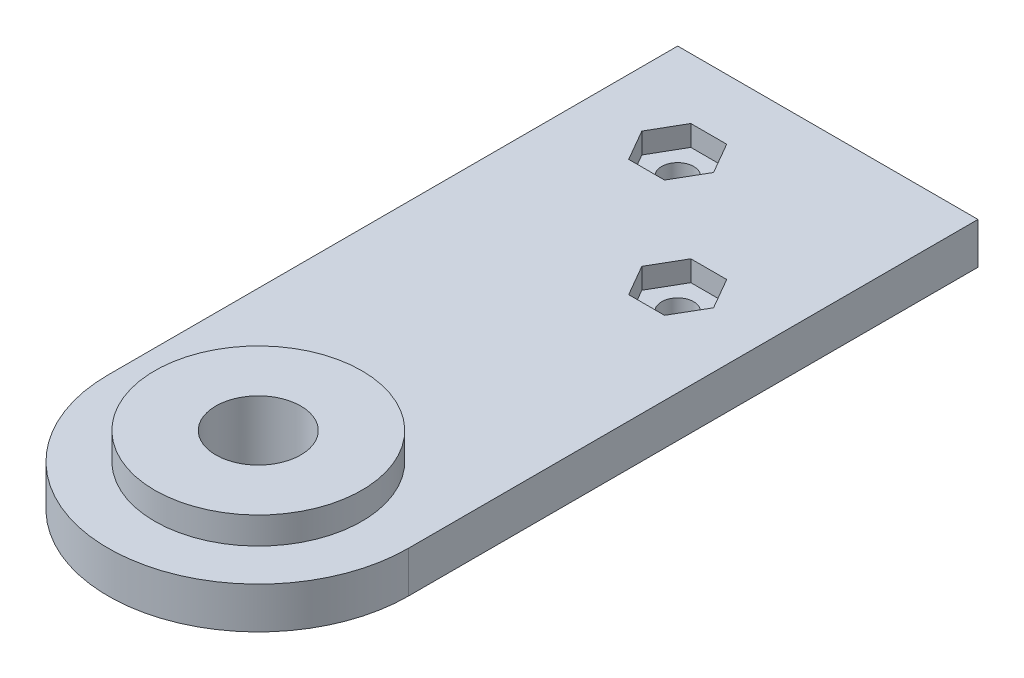
SolidWorks part; units mm, degrees
ref_plane "Front Plane" through (0, 0, 0) normal (0, 0, 1) x (1, 0, 0)
ref_plane "Top Plane" through (0, 0, 0) normal (0, 1, 0) x (1, 0, 0)
ref_plane "Right Plane" through (0, 0, 0) normal (1, 0, 0) x (0, 0, -1)
sketch "Sketch1" plane through (0, 0, 0) normal (0, 1, 0) x (1, 0, 0)
  line L1 (-46.1225, -21.4958) -> (3.8775, -21.4958)
  line L2 (-46.1225, -21.4958) -> (-46.1225, -71.4958)
  line L3 (-46.1225, -71.4958) -> (3.8775, -71.4958)
  line L4 (3.8775, -21.4958) -> (3.8775, -71.4958)
  dimension "D1" = 50
  dimension "D2" = 50
extrude "Boss-Extrude1" add sketch "Sketch1" along normal blind 4
sketch "Sketch2" plane through (0, 0, 0) normal (0, -1, 0) x (1, 0, 0)
  line L0 (3.8775, 71.4958) -> (3.8775, 21.4958) construction
  line L1 (-46.1225, 71.4958) -> (3.8775, 71.4958) construction
  circle A0 centre (-21.1225, 46.4958) radius 4.1
  point P5 (3.8775, 46.4958)
  point P9 (-21.1225, 71.4958)
  dimension "D1" = 8.2
extrude "Cut-Extrude1" cut sketch "Sketch2" against normal up to surface (4 mm away) up to face at (-21.1225, 4, 46.4958)
sketch "Sketch5" plane through (0, 4, 0) normal (0, 1, 0) x (1, 0, 0)
  circle A0 centre (-21.1225, -46.4958) radius 10
  circle A1 centre (-21.1225, -46.4958) radius 4.1
  dimension "D1" = 20
  dimension "D2" = 8.2
extrude "Boss-Extrude4" add sketch "Sketch5" along normal blind 2.6
sketch "Sketch6" plane through (0, 0, 0) normal (0, -1, 0) x (1, 0, 0)
  line L0 (-35.6225, 46.4958) -> (-35.6225, 21.4958)
  line L1 (3.8775, 21.4958) -> (-46.1225, 21.4958) construction
  line L2 (-35.6225, 21.4958) -> (-6.6225, 21.4958)
  line L3 (-6.6225, 21.4958) -> (-6.6225, 46.4958)
  arc A0 (-6.6225, 46.4958) -> (-35.6225, 46.4958) centre (-21.1225, 46.4958) ccw
extrude "Cut-Extrude3" cut sketch "Sketch6" against normal up to surface (4 mm away) flip side to cut up to face at (-21.1225, 4, 46.4958)
sketch "Sketch7" plane through (0, 0, 21.4958) normal (0, 0, -1) x (-1, 0, 0)
  line L4 (6.6225, 4) -> (6.6225, 0)
  line L5 (6.6225, 0) -> (35.6225, 0)
  line L6 (35.6225, 0) -> (35.6225, 4)
  line L7 (35.6225, 4) -> (6.6225, 4)
  line L8 (6.6225, 4) -> (6.6225, 0)
  line L9 (6.6225, 0) -> (35.6225, 0)
  line L10 (35.6225, 0) -> (35.6225, 4)
  line L11 (35.6225, 4) -> (6.6225, 4)
  dimension "D1" = 0
extrude "Boss-Extrude5" add sketch "Sketch7" along normal blind 30
sketch "Sketch8" plane through (0, 4, 0) normal (0, 1, 0) x (1, 0, 0)
  line L0 (-35.6225, 8.5042) -> (-6.6225, -20.4958) construction
  line L1 (-6.6225, 8.5042) -> (-6.6225, -46.4958) construction
  line L2 (-15.4657, -11.6526) -> (-21.1225, -5.9958) construction
  line L3 (-21.1225, -5.9958) -> (-26.7794, -0.3389) construction
  line L4 (-35.6225, 8.5042) -> (-6.6225, 8.5042) construction
  circle A0 centre (-26.7794, -0.3389) radius 1.55
  circle A1 centre (-15.4657, -11.6526) radius 1.55
  point P5 (-21.1225, -5.9958)
  dimension "D1" = 3.1
  dimension "D2" = 29
  dimension "D3" = 8
  dimension "D4" = 8
extrude "Cut-Extrude4" cut sketch "Sketch8" against normal up to surface (4 mm away) up to face at (-21.1225, 0, 42.3958)
sketch "Sketch9" plane through (0, 4, 0) normal (0, 1, 0) x (1, 0, 0)
  line L1 (-25.0473, 2.6611) -> (-28.5114, 2.6611)
  line L2 (-28.5114, 2.6611) -> (-30.2435, -0.3389)
  line L3 (-30.2435, -0.3389) -> (-28.5114, -3.3389)
  line L4 (-28.5114, -3.3389) -> (-25.0473, -3.3389)
  line L5 (-25.0473, -3.3389) -> (-23.3153, -0.3389)
  line L6 (-23.3153, -0.3389) -> (-25.0473, 2.6611)
  line L7 (-13.7336, -8.6526) -> (-17.1977, -8.6526)
  line L8 (-17.1977, -8.6526) -> (-18.9298, -11.6526)
  line L9 (-18.9298, -11.6526) -> (-17.1977, -14.6526)
  line L10 (-17.1977, -14.6526) -> (-13.7336, -14.6526)
  line L11 (-13.7336, -14.6526) -> (-12.0016, -11.6526)
  line L12 (-12.0016, -11.6526) -> (-13.7336, -8.6526)
  circle A0 centre (-26.7794, -0.3389) radius 3 construction
  circle A1 centre (-15.4657, -11.6526) radius 3 construction
extrude "Cut-Extrude5" cut sketch "Sketch9" against normal blind 2
